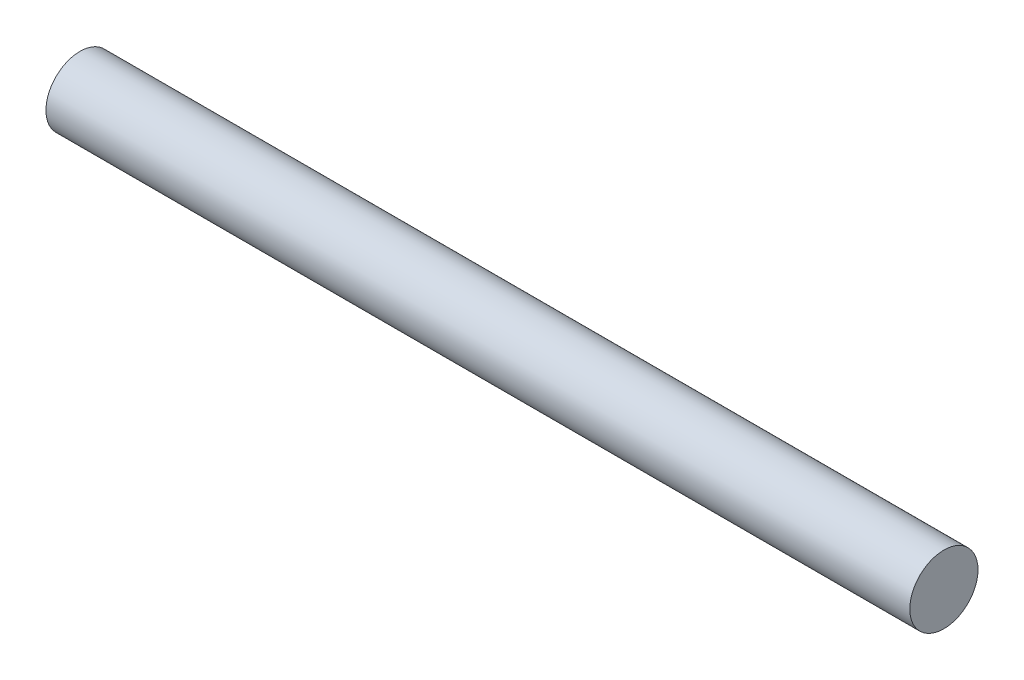
SolidWorks part; units mm, degrees
material "6061 Alloy"
ref_plane "Front Plane" through (0, 0, 0) normal (0, 0, 1) x (1, 0, 0)
ref_plane "Top Plane" through (0, 0, 0) normal (0, 1, 0) x (1, 0, 0)
ref_plane "Right Plane" through (0, 0, 0) normal (1, 0, 0) x (0, 0, -1)
sketch "Sketch1" plane through (0, 0, 0) normal (1, 0, 0) x (0, 0, -1)
  circle A1 centre (0, 0) radius 4.7625
  dimension "D1" = 9.525
extrude "Boss-Extrude1" add sketch "Sketch1" along normal blind 120.65
move or copy body "Body-Move/Copy1" bodies to move or copy 103
